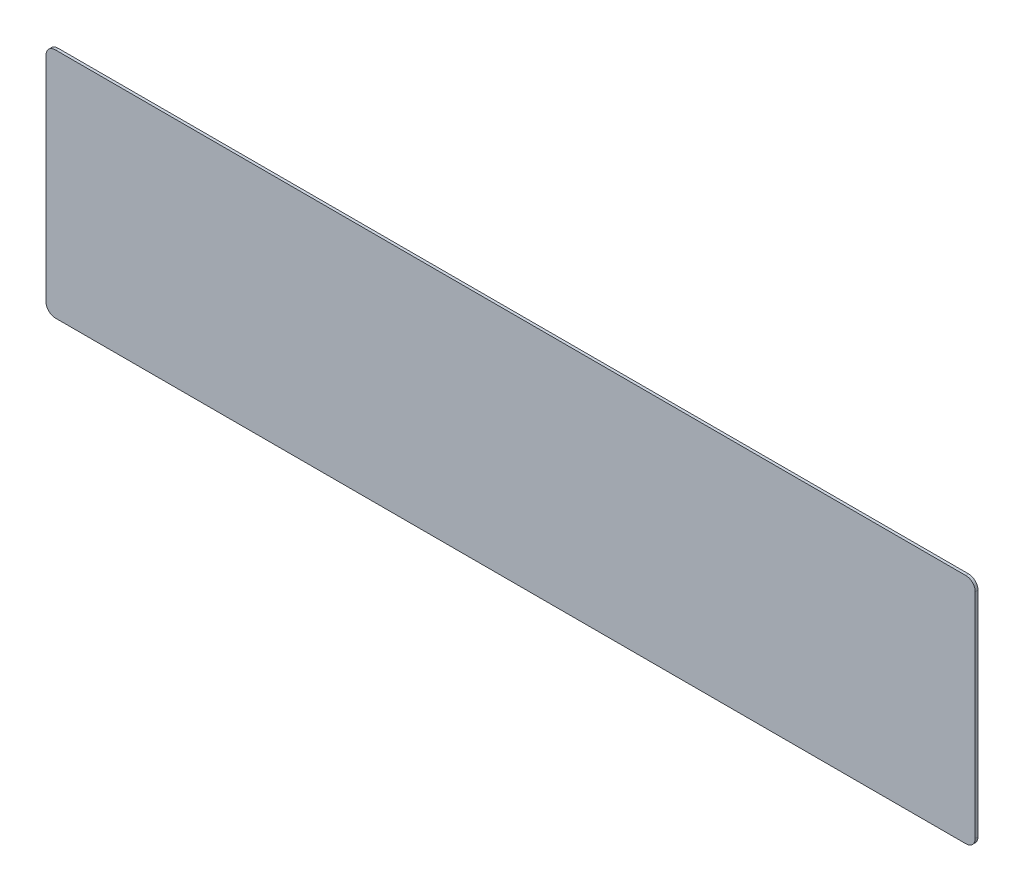
SolidWorks part; units mm, degrees
ref_plane "Plan de face" through (0, 0, 0) normal (0, 0, 1) x (1, 0, 0)
ref_plane "Plan de dessus" through (0, 0, 0) normal (0, 1, 0) x (1, 0, 0)
ref_plane "Plan de droite" through (0, 0, 0) normal (1, 0, 0) x (0, 0, -1)
sketch "Esquisse1" plane through (0, 0, 0) normal (0, 0, 1) x (1, 0, 0)
  line L1 (204.7789, 142.0715) -> (204.7789, -117.1883) construction
  line L3 (694.7789, -116.4628) -> (-285.2211, -116.4628)
  line L4 (704.7789, -106.4628) -> (704.7789, 123.5372)
  line L5 (694.7789, 133.5372) -> (-285.2211, 133.5372)
  line L6 (-295.2211, -106.4628) -> (-295.2211, 123.5372)
  line L7 (699.6693, -115.1854) -> (-290.1116, 132.2598) construction
  line L8 (699.6693, 132.2598) -> (-290.1116, -115.1854) construction
  line L512 (527.8002, 133.5372) -> (527.8002, -116.4628) construction
  line L513 (527.8002, 8.5372) -> (704.7789, 8.5372) construction
  line L514 (616.2895, 133.5372) -> (616.2895, -116.4628) construction
  arc A12 (694.7789, -116.4628) -> (704.7789, -106.4628) centre (694.7789, -106.4628) ccw
  arc A13 (704.7789, 123.5372) -> (694.7789, 133.5372) centre (694.7789, 123.5372) ccw
  arc A14 (-285.2211, -116.4628) -> (-295.2211, -106.4628) centre (-285.2211, -106.4628) cw
  arc A15 (-295.2211, 123.5372) -> (-285.2211, 133.5372) centre (-285.2211, 123.5372) cw
  dimension "D8" = 10
extrude "Boss.-Extru.1" add sketch "Esquisse1" along normal blind 3
